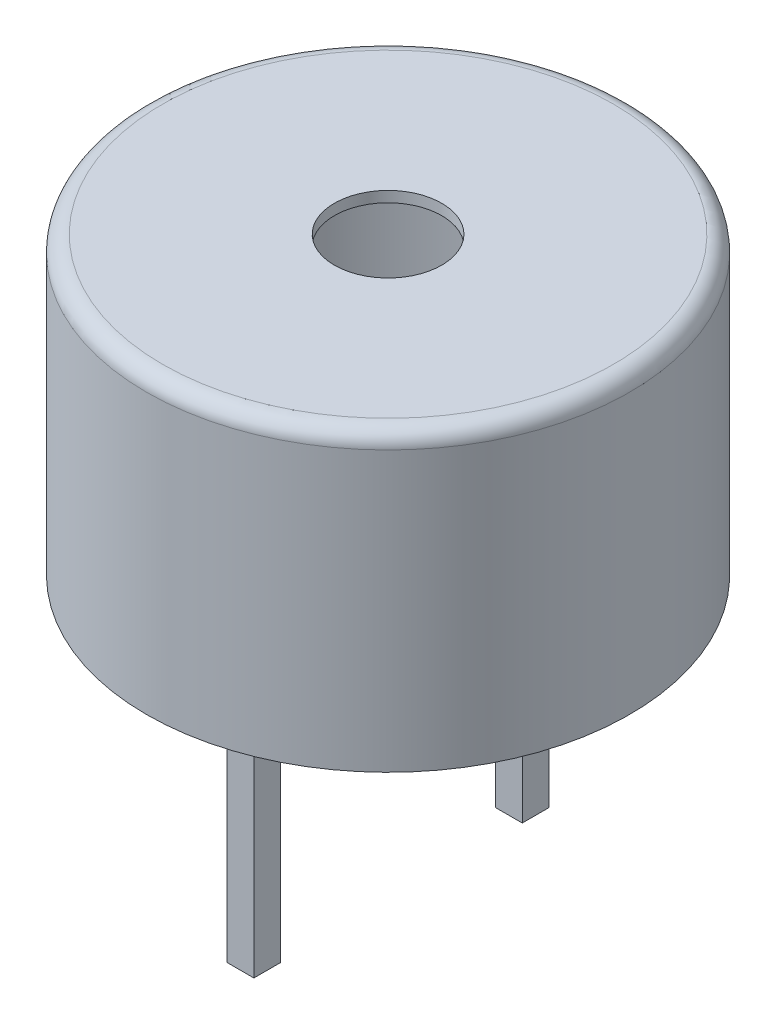
SolidWorks part; units mm, degrees
ref_plane "Alzado" through (0, 0, 0) normal (0, 0, 1) x (1, 0, 0)
ref_plane "Planta" through (0, 0, 0) normal (0, 1, 0) x (1, 0, 0)
ref_plane "Vista lateral" through (0, 0, 0) normal (1, 0, 0) x (0, 0, -1)
sketch "Croquis1" plane through (0, 0, 0) normal (0, 1, 0) x (1, 0, 0)
  circle A0 centre (0, 0) radius 4.5
  dimension "D1" = 9
extrude "Saliente-Extruir1" add sketch "Croquis1" along normal blind 1
sketch "Croquis2" plane through (0, 1, 0) normal (0, 1, 0) x (1, 0, 0)
  circle A2 centre (0, 0) radius 3.5
  circle A3 centre (0, 0) radius 3.5
  circle A4 centre (0, 0) radius 4.5
  circle A5 centre (0, 0) radius 4.5
  dimension "D1" = 1
  dimension "D2" = 0
extrude "Saliente-Extruir2" add sketch "Croquis2" along normal blind 4.5
sketch "Croquis3" plane through (0, 1, 0) normal (0, 1, 0) x (1, 0, 0)
  circle A0 centre (0, 0) radius 2.2964
extrude "Saliente-Extruir3" add sketch "Croquis3" along normal blind 2
sketch "Croquis4" plane through (0, 5.5, 0) normal (0, 1, 0) x (1, 0, 0)
  circle A0 centre (0, 0) radius 1
  circle A1 centre (0, 0) radius 4.5
  circle A2 centre (0, 0) radius 4.5
  dimension "D2" = 2
  dimension "D1" = 0
extrude "Saliente-Extruir4" add sketch "Croquis4" against normal blind 0.2
sketch "Croquis5" plane through (0, 0, 0) normal (0, -1, 0) x (1, 0, 0)
  line L0 (0, -2.5) -> (0, 2.5) construction
  line L1 (0, 0) -> (2.1284, 0) construction
  line L2 (0.25, -2.75) -> (-0.25, -2.75)
  line L3 (0.25, -2.75) -> (0.25, -2.25)
  line L4 (0.25, -2.25) -> (-0.25, -2.25)
  line L5 (-0.25, -2.75) -> (-0.25, -2.25)
  line L6 (0.25, -2.75) -> (-0.25, -2.25) construction
  line L7 (0.25, -2.25) -> (-0.25, -2.75) construction
  line L8 (0.25, 2.25) -> (-0.25, 2.75) construction
  line L9 (0.25, 2.75) -> (-0.25, 2.25) construction
  line L10 (-0.25, 2.75) -> (-0.25, 2.25)
  line L11 (0.25, 2.25) -> (-0.25, 2.25)
  line L12 (0.25, 2.75) -> (0.25, 2.25)
  line L13 (0.25, 2.75) -> (-0.25, 2.75)
  point P2 (0, 0)
  dimension "D1" = 5
  dimension "D2" = 0.5
  dimension "D3" = 0.5
extrude "Saliente-Extruir5" add sketch "Croquis5" along normal blind 5
fillet "Redondeo1" radius 0.3 1 edges at (0, 5.5, 4.5)
